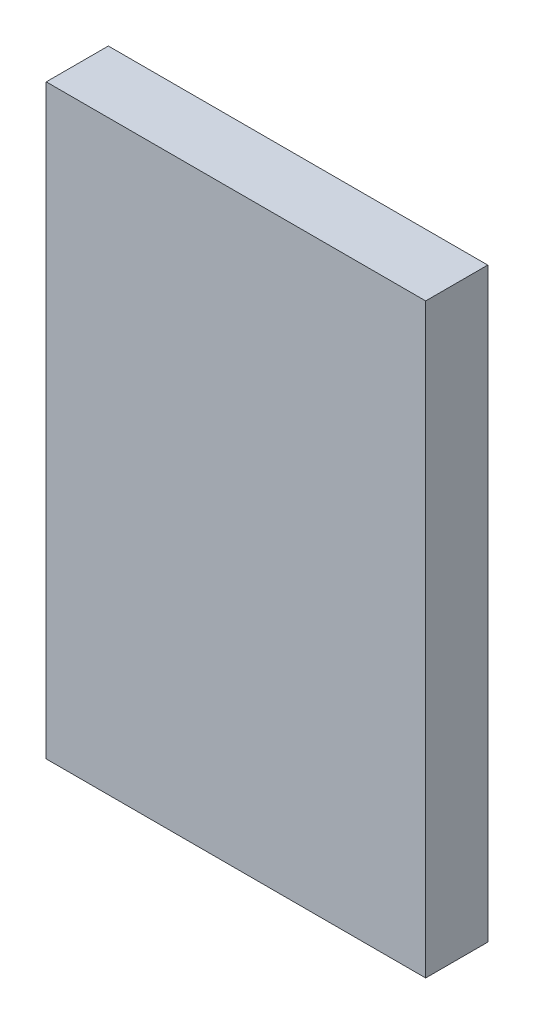
SolidWorks part; units mm, degrees
ref_plane "Plan de face" through (0, 0, 0) normal (0, 0, 1) x (1, 0, 0)
ref_plane "Plan de dessus" through (0, 0, 0) normal (0, 1, 0) x (1, 0, 0)
ref_plane "Plan de droite" through (0, 0, 0) normal (1, 0, 0) x (0, 0, -1)
sketch "Esquisse1" plane through (0, 0, 0) normal (0, 0, 1) x (1, 0, 0)
  line L1 (-27.5, -42.5) -> (27.5, -42.5)
  line L2 (-27.5, -42.5) -> (-27.5, 42.5)
  line L3 (-27.5, 42.5) -> (27.5, 42.5)
  line L4 (27.5, -42.5) -> (27.5, 42.5)
  line L5 (-27.5, -42.5) -> (27.5, 42.5) construction
  line L6 (-27.5, 42.5) -> (27.5, -42.5) construction
  point P0 (0, 0)
  dimension "D1" = 55
  dimension "D2" = 85
extrude "Boss.-Extru.1" add sketch "Esquisse1" along normal blind 9
